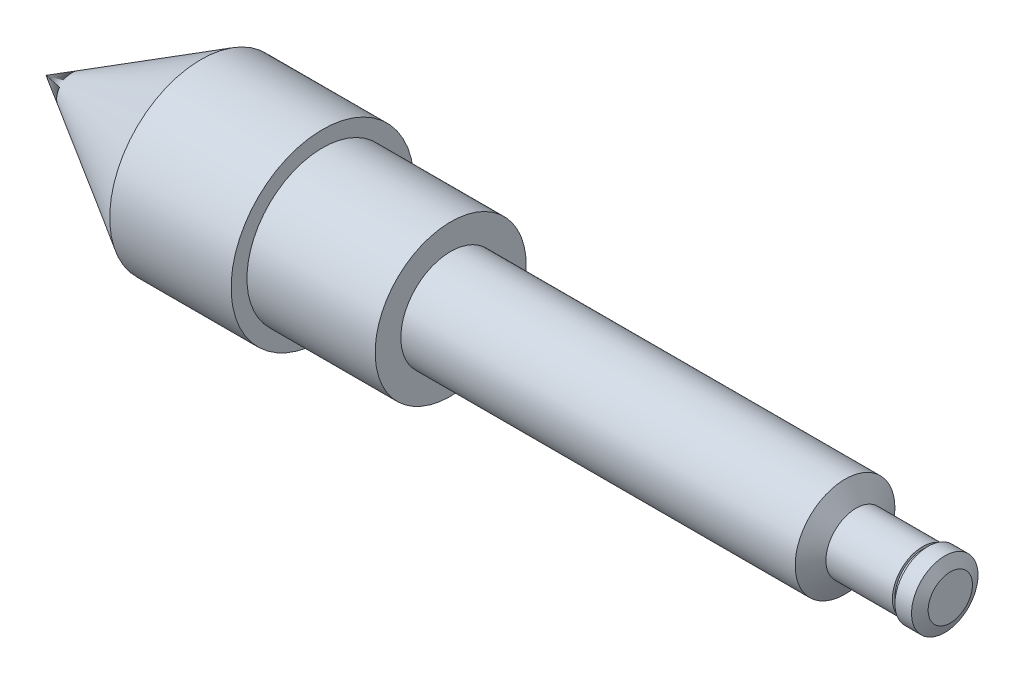
SolidWorks part; units mm, degrees
ref_plane "Front Plane" through (0, 0, 0) normal (0, 0, 1) x (1, 0, 0)
ref_plane "Top Plane" through (0, 0, 0) normal (0, 1, 0) x (1, 0, 0)
ref_plane "Right Plane" through (0, 0, 0) normal (1, 0, 0) x (0, 0, -1)
sketch "Sketch1" plane through (0, 0, 0) normal (0, 1, 0) x (1, 0, 0)
  line L0 (0, -18.15) -> (-30.8, 0)
  line L1 (-55, 0) -> (55, 0) construction
  line L2 (0, -18.15) -> (24.1, -18.15)
  line L3 (24.1, -18.15) -> (24.1, -15)
  line L4 (24.1, -15) -> (49.55, -15)
  line L5 (49.55, -9.9) -> (127.85, -9.9)
  line L6 (127.85, -9.9) -> (130.05, -6)
  line L7 (130.05, -6) -> (143.25, -6)
  line L8 (143.25, -6) -> (143.25, -5.5)
  line L9 (143.25, -5.5) -> (144.35, -5.5)
  line L10 (144.35, -5.5) -> (144.35, -6.6)
  line L11 (144.35, -6.6) -> (147.65, -6.6)
  line L12 (147.65, -6.6) -> (148.75, -4.4)
  line L13 (148.75, -4.4) -> (148.75, 0)
  line L14 (49.55, -9.9) -> (49.55, -15)
  line L15 (148.75, 0) -> (-30.8, 0)
  dimension "D1" = 24.1
  dimension "D2" = 9.9
  dimension "D3" = 18.15
  dimension "D4" = 25.45
  dimension "D5" = 78.3
  dimension "D6" = 13.2
  dimension "D7" = 3.3
  dimension "D8" = 2.2
  dimension "D9" = 1.1
  dimension "D10" = 1.1
  dimension "D11" = 6
  dimension "D12" = 15
  dimension "D13" = 5.5
  dimension "D14" = 6.6
  dimension "D15" = 30.8
  dimension "D16" = 4.4
  dimension "D17" = 0
revolve "Revolve1" add sketch "Sketch1" angle 360 about L15
